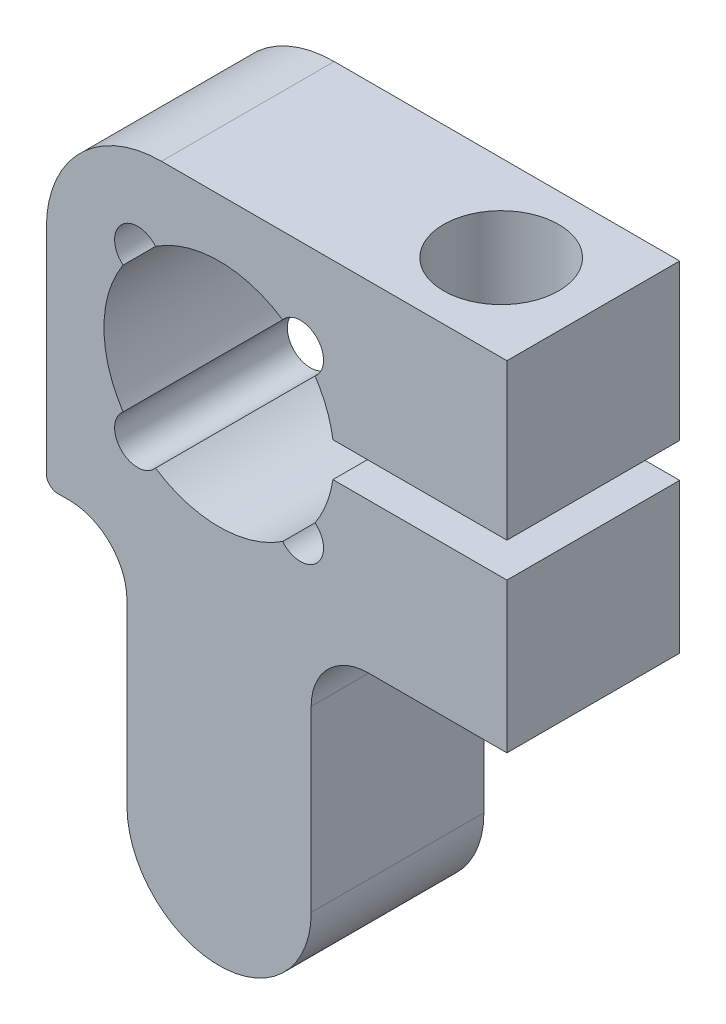
SolidWorks part; units mm, degrees
ref_plane "前视基准面" through (0, 0, 0) normal (0, 0, 1) x (1, 0, 0)
ref_plane "上视基准面" through (0, 0, 0) normal (0, 1, 0) x (1, 0, 0)
ref_plane "右视基准面" through (0, 0, 0) normal (1, 0, 0) x (0, 0, -1)
sketch "草图1" plane through (0, 0, 0) normal (0, 0, 1) x (1, 0, 0)
  line L48 (1152.2167, 1050.8588) -> (1178.2999, 1050.8588) construction
  line L49 (1165.7257, 1104.4441) -> (1165.7257, 1037.68) construction
  line L50 (1143.0162, 1085.8588) -> (1197.2507, 1085.8588) construction
  line L51 (1175.6125, 1087.3588) -> (1190.7257, 1087.3588)
  line L52 (1175.6125, 1084.3588) -> (1190.7257, 1084.3588)
  line L53 (1182.7257, 1102.9823) -> (1182.7257, 1068.9018) construction
  line L54 (1190.7257, 1100.8588) -> (1190.7257, 1087.3588)
  line L55 (1190.7257, 1084.3588) -> (1190.7257, 1071.3588)
  line L79 (1190.7257, 1100.8588) -> (1160.7257, 1100.8588)
  line L80 (1150.7257, 1072.3588) -> (1150.7257, 1090.8588)
  line L89 (1173.7257, 1050.8588) -> (1173.7257, 1066.3588)
  line L90 (1157.7257, 1050.8588) -> (1157.7257, 1066.3588)
  line L91 (1190.7257, 1071.3588) -> (1178.7257, 1071.3588)
  line L92 (1152.7257, 1071.3588) -> (1151.7257, 1071.3588)
  line L98 (1165.7257, 1085.8588) -> (1155.53, 1096.0545) construction
  arc A4 (1175.6125, 1087.3588) -> (1174.0624, 1091.3813) centre (1165.7257, 1085.8588) ccw
  arc A5 (1160.2031, 1077.5221) -> (1171.2482, 1077.5221) centre (1165.7257, 1085.8588) ccw
  arc A6 (1174.0624, 1080.3363) -> (1175.6125, 1084.3588) centre (1165.7257, 1085.8588) ccw
  arc A7 (1171.2482, 1094.1956) -> (1160.2031, 1094.1956) centre (1165.7257, 1085.8588) ccw
  arc A8 (1157.3889, 1091.3813) -> (1157.3889, 1080.3363) centre (1165.7257, 1085.8588) ccw
  arc A9 (1160.2031, 1094.1956) -> (1157.3889, 1091.3813) centre (1158.6546, 1092.9299) ccw
  arc A10 (1157.3889, 1080.3363) -> (1160.2031, 1077.5221) centre (1158.6546, 1078.7878) ccw
  arc A11 (1171.2482, 1077.5221) -> (1174.0624, 1080.3363) centre (1172.7967, 1078.7878) ccw
  arc A12 (1174.0624, 1091.3813) -> (1171.2482, 1094.1956) centre (1172.7967, 1092.9299) ccw
  arc A13 (1160.7257, 1100.8588) -> (1150.7257, 1090.8588) centre (1160.7257, 1090.8588) ccw
  arc A14 (1157.7257, 1050.8588) -> (1173.7257, 1050.8588) centre (1165.7257, 1050.8588) ccw
  arc A15 (1178.7257, 1071.3588) -> (1173.7257, 1066.3588) centre (1178.7257, 1066.3588) ccw
  arc A16 (1157.7257, 1066.3588) -> (1152.7257, 1071.3588) centre (1152.7257, 1066.3588) ccw
  arc A17 (1150.7257, 1072.3588) -> (1151.7257, 1071.3588) centre (1151.7257, 1072.3588) ccw
extrude "拉伸1" add sketch "草图1" along normal blind 15
sketch "草图2" plane through (0, 1100.8588, 0) normal (0, 1, 0) x (1, 0, 0)
  line L0 (1150.7257, -15) -> (1150.7257, 0) construction
  line L1 (1190.7257, 0) -> (1160.7257, 0) construction
  circle A0 centre (1182.7257, -7.5) radius 3.4
  dimension "D1" = 6.8
  dimension "D3" = 7.5
  dimension "D2" = 32
extrude "拉伸2" cut sketch "草图2" against normal through all
sketch "草图3" plane through (0, 1100.8588, 0) normal (0, 1, 0) x (1, 0, 0)
  circle A0 centre (1182.7257, -7.5) radius 5
  dimension "D1" = 10
extrude "拉伸3" cut sketch "草图3" against normal blind 14
